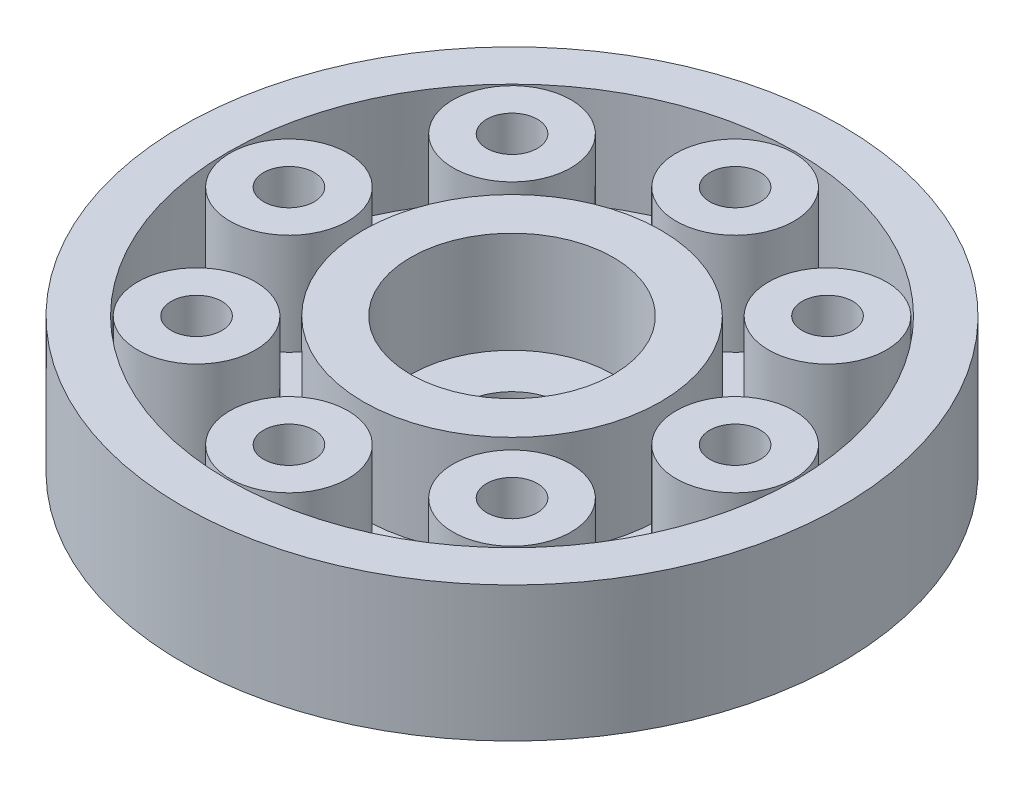
SolidWorks part; units mm, degrees
ref_plane "前视基准面" through (0, 0, 0) normal (0, 0, 1) x (1, 0, 0)
ref_plane "上视基准面" through (0, 0, 0) normal (0, 1, 0) x (1, 0, 0)
ref_plane "右视基准面" through (0, 0, 0) normal (1, 0, 0) x (0, 0, -1)
sketch "草图1" plane through (0, 0, 0) normal (0, 1, 0) x (1, 0, 0)
  circle A0 centre (0.3947, -0.592) radius 9.75
  arc A1 (-0.0261, 2.2521) -> (-0.4282, 2.7466) centre (-1.4141, 1.5344) ccw
  arc A2 (0.0949, 2.2673) -> (-0.0261, 2.2521) centre (0.3947, -0.592) ccw
  arc A3 (0.3614, 2.8463) -> (0.0949, 2.2673) centre (1.6177, 1.9174) ccw
  arc A4 (0.4279, 2.8463) -> (0.3614, 2.8463) centre (0.3947, -0.592) ccw
  arc A5 (0.6944, 2.2673) -> (0.4279, 2.8463) centre (-0.8284, 1.9174) ccw
  arc A6 (0.8154, 2.2521) -> (0.6944, 2.2673) centre (0.3947, -0.592) ccw
  arc A7 (1.2175, 2.7466) -> (0.8154, 2.2521) centre (2.2034, 1.5344) ccw
  arc A8 (1.282, 2.73) -> (1.2175, 2.7466) centre (0.3947, -0.592) ccw
  arc A9 (1.3961, 2.103) -> (1.282, 2.73) centre (-0.1659, 2.1427) ccw
  arc A10 (1.5095, 2.0581) -> (1.3961, 2.103) centre (0.3947, -0.592) ccw
  arc A11 (2.0219, 2.4371) -> (1.5095, 2.0581) centre (2.6754, 1.0178) ccw
  arc A12 (2.0803, 2.405) -> (2.0219, 2.4371) centre (0.3947, -0.592) ccw
  arc A13 (2.0348, 1.7693) -> (2.0803, 2.405) centre (0.5318, 2.1962) ccw
  arc A14 (2.1335, 1.6976) -> (2.0348, 1.7693) centre (0.3947, -0.592) ccw
  arc A15 (2.7241, 1.9372) -> (2.1335, 1.6976) centre (3.004, 0.4) ccw
  arc A16 (2.7726, 1.8917) -> (2.7241, 1.9372) centre (0.3947, -0.592) ccw
  arc A17 (2.5705, 1.2872) -> (2.7726, 1.8917) centre (1.2209, 2.0745) ccw
  arc A18 (2.6483, 1.1932) -> (2.5705, 1.2872) centre (0.3947, -0.592) ccw
  arc A19 (3.2799, 1.2785) -> (2.6483, 1.1932) centre (3.1688, -0.2801) ccw
  arc A20 (3.3156, 1.2223) -> (3.2799, 1.2785) centre (0.3947, -0.592) ccw
  arc A21 (2.9695, 0.687) -> (3.3156, 1.2223) centre (1.858, 1.7853) ccw
  arc A22 (3.0214, 0.5766) -> (2.9695, 0.687) centre (0.3947, -0.592) ccw
  arc A23 (3.6544, 0.5022) -> (3.0214, 0.5766) centre (3.1592, -0.9798) ccw
  arc A24 (3.675, 0.4389) -> (3.6544, 0.5022) centre (0.3947, -0.592) ccw
  arc A25 (3.2067, 0.0065) -> (3.675, 0.4389) centre (2.4033, 1.3467) ccw
  arc A26 (3.2295, -0.1133) -> (3.2067, 0.0065) centre (0.3947, -0.592) ccw
  arc A27 (3.8241, -0.3429) -> (3.2295, -0.1133) centre (2.9759, -1.6551) ccw
  arc A28 (3.8283, -0.4093) -> (3.8241, -0.3429) centre (0.3947, -0.592) ccw
  arc A29 (3.2672, -0.7116) -> (3.8283, -0.4093) centre (2.8223, 0.7862) ccw
  arc A30 (3.2595, -0.8334) -> (3.2672, -0.7116) centre (0.3947, -0.592) ccw
  arc A31 (3.7783, -1.2036) -> (3.2595, -0.8334) centre (2.6304, -2.2636) ccw
  arc A32 (3.7659, -1.269) -> (3.7783, -1.2036) centre (0.3947, -0.592) ccw
  arc A33 (3.1472, -1.4222) -> (3.7659, -1.269) centre (3.0888, 0.1392) ccw
  arc A34 (3.1095, -1.5382) -> (3.1472, -1.4222) centre (0.3947, -0.592) ccw
  arc A35 (3.5199, -2.0259) -> (3.1095, -1.5382) centre (2.1445, -2.7671) ccw
  arc A36 (3.4916, -2.0861) -> (3.5199, -2.0259) centre (0.3947, -0.592) ccw
  arc A37 (2.8542, -2.0806) -> (3.4916, -2.0861) centre (3.186, -0.5538) ccw
  arc A38 (2.7889, -2.1837) -> (2.8542, -2.0806) centre (0.3947, -0.592) ccw
  arc A39 (3.0652, -2.758) -> (2.7889, -2.1837) centre (1.5486, -3.1339) ccw
  arc A40 (3.0227, -2.8093) -> (3.0652, -2.758) centre (0.3947, -0.592) ccw
  arc A41 (2.4068, -2.6455) -> (3.0227, -2.8093) centre (3.1078, -1.2491) ccw
  arc A42 (2.3178, -2.7291) -> (2.4068, -2.6455) centre (0.3947, -0.592) ccw
  arc A43 (2.4426, -3.3541) -> (2.3178, -2.7291) centre (0.8801, -3.341) ccw
  arc A44 (2.3887, -3.3932) -> (2.4426, -3.3541) centre (0.3947, -0.592) ccw
  arc A45 (1.8329, -3.0814) -> (2.3887, -3.3932) centre (2.8591, -1.9032) ccw
  arc A46 (1.7259, -3.1402) -> (1.8329, -3.0814) centre (0.3947, -0.592) ccw
  arc A47 (1.6913, -3.7766) -> (1.7259, -3.1402) centre (0.1812, -3.3754) ccw
  arc A48 (1.6295, -3.8011) -> (1.6913, -3.7766) centre (0.3947, -0.592) ccw
  arc A49 (1.1686, -3.3609) -> (1.6295, -3.8011) centre (2.4556, -2.4749) ccw
  arc A50 (1.0504, -3.3912) -> (1.1686, -3.3609) centre (0.3947, -0.592) ccw
  arc A51 (0.8586, -3.999) -> (1.0504, -3.3912) centre (-0.5043, -3.2349) ccw
  arc A52 (0.7926, -4.0074) -> (0.8586, -3.999) centre (0.3947, -0.592) ccw
  arc A53 (0.4557, -3.4663) -> (0.7926, -4.0074) centre (1.9226, -2.9283) ccw
  arc A54 (0.3337, -3.4663) -> (0.4557, -3.4663) centre (0.3947, -0.592) ccw
  arc A55 (-0.0033, -4.0074) -> (0.3337, -3.4663) centre (-1.1333, -2.9283) ccw
  arc A56 (-0.0693, -3.999) -> (-0.0033, -4.0074) centre (0.3947, -0.592) ccw
  arc A57 (-0.2611, -3.3912) -> (-0.0693, -3.999) centre (1.2936, -3.2349) ccw
  arc A58 (-0.3793, -3.3609) -> (-0.2611, -3.3912) centre (0.3947, -0.592) ccw
  arc A59 (-0.8401, -3.8011) -> (-0.3793, -3.3609) centre (-1.6663, -2.4749) ccw
  arc A60 (-0.902, -3.7766) -> (-0.8401, -3.8011) centre (0.3947, -0.592) ccw
  arc A61 (-0.9366, -3.1402) -> (-0.902, -3.7766) centre (0.6081, -3.3754) ccw
  arc A62 (-1.0435, -3.0814) -> (-0.9366, -3.1402) centre (0.3947, -0.592) ccw
  arc A63 (-1.5994, -3.3932) -> (-1.0435, -3.0814) centre (-2.0698, -1.9032) ccw
  arc A64 (-1.6533, -3.3541) -> (-1.5994, -3.3932) centre (0.3947, -0.592) ccw
  arc A65 (-1.5285, -2.7291) -> (-1.6533, -3.3541) centre (-0.0908, -3.341) ccw
  arc A66 (-1.6174, -2.6455) -> (-1.5285, -2.7291) centre (0.3947, -0.592) ccw
  arc A67 (-2.2334, -2.8093) -> (-1.6174, -2.6455) centre (-2.3185, -1.2491) ccw
  arc A68 (-2.2758, -2.758) -> (-2.2334, -2.8093) centre (0.3947, -0.592) ccw
  arc A69 (-1.9995, -2.1837) -> (-2.2758, -2.758) centre (-0.7592, -3.1339) ccw
  arc A70 (-2.0649, -2.0806) -> (-1.9995, -2.1837) centre (0.3947, -0.592) ccw
  arc A71 (-2.7023, -2.0861) -> (-2.0649, -2.0806) centre (-2.3967, -0.5538) ccw
  arc A72 (-2.7306, -2.0259) -> (-2.7023, -2.0861) centre (0.3947, -0.592) ccw
  arc A73 (-2.3202, -1.5382) -> (-2.7306, -2.0259) centre (-1.3551, -2.7671) ccw
  arc A74 (-2.3579, -1.4222) -> (-2.3202, -1.5382) centre (0.3947, -0.592) ccw
  arc A75 (-2.9765, -1.269) -> (-2.3579, -1.4222) centre (-2.2995, 0.1392) ccw
  arc A76 (-2.989, -1.2036) -> (-2.9765, -1.269) centre (0.3947, -0.592) ccw
  arc A77 (-2.4702, -0.8334) -> (-2.989, -1.2036) centre (-1.8411, -2.2636) ccw
  arc A78 (-2.4779, -0.7116) -> (-2.4702, -0.8334) centre (0.3947, -0.592) ccw
  arc A79 (-3.039, -0.4093) -> (-2.4779, -0.7116) centre (-2.033, 0.7862) ccw
  arc A80 (-3.0348, -0.3429) -> (-3.039, -0.4093) centre (0.3947, -0.592) ccw
  arc A81 (-2.4402, -0.1133) -> (-3.0348, -0.3429) centre (-2.1866, -1.6551) ccw
  arc A82 (-2.4173, 0.0065) -> (-2.4402, -0.1133) centre (0.3947, -0.592) ccw
  arc A83 (-2.8857, 0.4389) -> (-2.4173, 0.0065) centre (-1.6139, 1.3467) ccw
  arc A84 (-2.8651, 0.5022) -> (-2.8857, 0.4389) centre (0.3947, -0.592) ccw
  arc A85 (-2.2321, 0.5766) -> (-2.8651, 0.5022) centre (-2.3699, -0.9798) ccw
  arc A86 (-2.1802, 0.687) -> (-2.2321, 0.5766) centre (0.3947, -0.592) ccw
  arc A87 (-2.5263, 1.2223) -> (-2.1802, 0.687) centre (-1.0687, 1.7853) ccw
  arc A88 (-2.4906, 1.2785) -> (-2.5263, 1.2223) centre (0.3947, -0.592) ccw
  arc A89 (-1.859, 1.1932) -> (-2.4906, 1.2785) centre (-2.3794, -0.2801) ccw
  arc A90 (-1.7812, 1.2872) -> (-1.859, 1.1932) centre (0.3947, -0.592) ccw
  arc A91 (-1.9833, 1.8917) -> (-1.7812, 1.2872) centre (-0.4315, 2.0745) ccw
  arc A92 (-1.9348, 1.9372) -> (-1.9833, 1.8917) centre (0.3947, -0.592) ccw
  arc A93 (-1.3442, 1.6976) -> (-1.9348, 1.9372) centre (-2.2147, 0.4) ccw
  arc A94 (-1.2455, 1.7693) -> (-1.3442, 1.6976) centre (0.3947, -0.592) ccw
  arc A95 (-1.2909, 2.405) -> (-1.2455, 1.7693) centre (0.2576, 2.1962) ccw
  arc A96 (-1.2326, 2.4371) -> (-1.2909, 2.405) centre (0.3947, -0.592) ccw
  arc A97 (-0.7202, 2.0581) -> (-1.2326, 2.4371) centre (-1.886, 1.0178) ccw
  arc A98 (-0.6067, 2.103) -> (-0.7202, 2.0581) centre (0.3947, -0.592) ccw
  arc A99 (-0.4927, 2.73) -> (-0.6067, 2.103) centre (0.9553, 2.1427) ccw
  arc A100 (-0.4282, 2.7466) -> (-0.4927, 2.73) centre (0.3947, -0.592) ccw
extrude "凸台-拉伸1" add sketch "草图1" along normal blind 3
ref_plane "基准面1" through (0, 0, 0) normal (0, -1, 0) x (-1, 0, 0)
sketch "草图2" plane through (0, 0, 0) normal (0, -1, 0) x (-1, 0, 0)
  line L0 (10.4941, -0.7442) -> (4.2859, -0.7442) construction
  circle A0 centre (-0.3947, -0.592) radius 9.75
extrude "凸台-拉伸2" add sketch "草图2" along normal blind 1
ref_plane "基准面2" through (0, 0, 0) normal (0, 1, 0) x (1, 0, 0)
sketch "草图4" plane through (0, 0, 0) normal (0, 1, 0) x (1, 0, 0)
  circle A0 centre (0.3947, -0.592) radius 1.5
extrude "切除-拉伸4" cut sketch "草图4" against normal blind 1
ref_plane "基准面3" through (0, 3, 0) normal (0, 1, 0) x (1, 0, 0)
sketch "草图5" plane through (0, 0, 0) normal (0, -1, 0) x (-1, 0, 0)
  circle A0 centre (-0.3947, -0.592) radius 4.4
  circle A1 centre (-0.3947, -0.592) radius 8.4
extrude "切除-拉伸5" cut sketch "草图5" against normal blind 10
sketch "草图6" plane through (0, 0, 0) normal (0, -1, 0) x (-1, 0, 0)
  line L0 (-0.3947, -0.592) -> (-0.3947, 7.808) construction
  circle A0 centre (-0.3947, -0.592) radius 6.6 construction
  circle A1 centre (-0.3947, -0.592) radius 8.4 construction
  circle A2 centre (-0.3947, 6.008) radius 0.75
  circle A3 centre (4.2722, 4.0749) radius 0.75
  circle A4 centre (6.2053, -0.592) radius 0.75
  circle A5 centre (4.2722, -5.2589) radius 0.75
  circle A6 centre (-0.3947, -7.192) radius 0.75
  circle A7 centre (-5.0616, -5.2589) radius 0.75
  circle A8 centre (-6.9947, -0.592) radius 0.75
  circle A9 centre (-5.0616, 4.0749) radius 0.75
  circle A10 centre (-0.3947, 6.008) radius 1.7445
  circle A11 centre (4.2722, 4.0749) radius 1.7445
  circle A12 centre (6.2053, -0.592) radius 1.7445
  circle A13 centre (4.2722, -5.2589) radius 1.7445
  circle A14 centre (-0.3947, -7.192) radius 1.7445
  circle A15 centre (-5.0616, -5.2589) radius 1.7445
  circle A16 centre (-6.9947, -0.592) radius 1.7445
  circle A17 centre (-5.0616, 4.0749) radius 1.7445
  point P26 (-0.3947, -0.592)
  point P42 (-0.3947, -0.592)
  dimension "D1" = 8
  dimension "D2" = 8
  dimension "D3" = 13.2
extrude "凸台-拉伸3" add sketch "草图6" against normal blind 3
ref_plane "基准面4" through (0, -1, 0) normal (0, -1, 0) x (-1, 0, 0)
sketch "草图7" plane through (0, -1, 0) normal (0, -1, 0) x (-1, 0, 0)
  circle A0 centre (-0.3947, 6.008) radius 0.75 construction
  circle A1 centre (-0.3947, -0.592) radius 1.5 construction
  circle A2 centre (-0.3947, 6.008) radius 0.75
  circle A3 centre (-0.3947, -0.592) radius 1.5
  circle A4 centre (4.2722, 4.0749) radius 0.75
  circle A5 centre (6.2053, -0.592) radius 0.75
  circle A6 centre (4.2722, -5.2589) radius 0.75
  circle A7 centre (-0.3947, -7.192) radius 0.75
  circle A8 centre (-5.0616, -5.2589) radius 0.75
  circle A9 centre (-6.9947, -0.592) radius 0.75
  circle A10 centre (-5.0616, 4.0749) radius 0.75
  point P23 (0, 0)
  point P24 (-0.3947, -0.592)
  dimension "D1" = 8
extrude "切除-拉伸6" cut sketch "草图7" against normal blind 3
ref_plane "基准面5" through (0, 3, 0) normal (0, 1, 0) x (1, 0, 0)
sketch "草图8" plane through (0, 3, 0) normal (0, 1, 0) x (1, 0, 0)
  circle A0 centre (0.3947, -0.592) radius 4
extrude "切除-拉伸7" cut sketch "草图8" against normal blind 3
ref_plane "基准面6" through (0, 0, 0) normal (0, 1, 0) x (1, 0, 0)
sketch "草图9" plane through (0, 0, 0) normal (0, 1, 0) x (1, 0, 0)
  circle A0 centre (0.3947, -0.592) radius 4
  circle A1 centre (0.3947, -0.592) radius 3
extrude "凸台-拉伸4" add sketch "草图9" along normal blind 3
